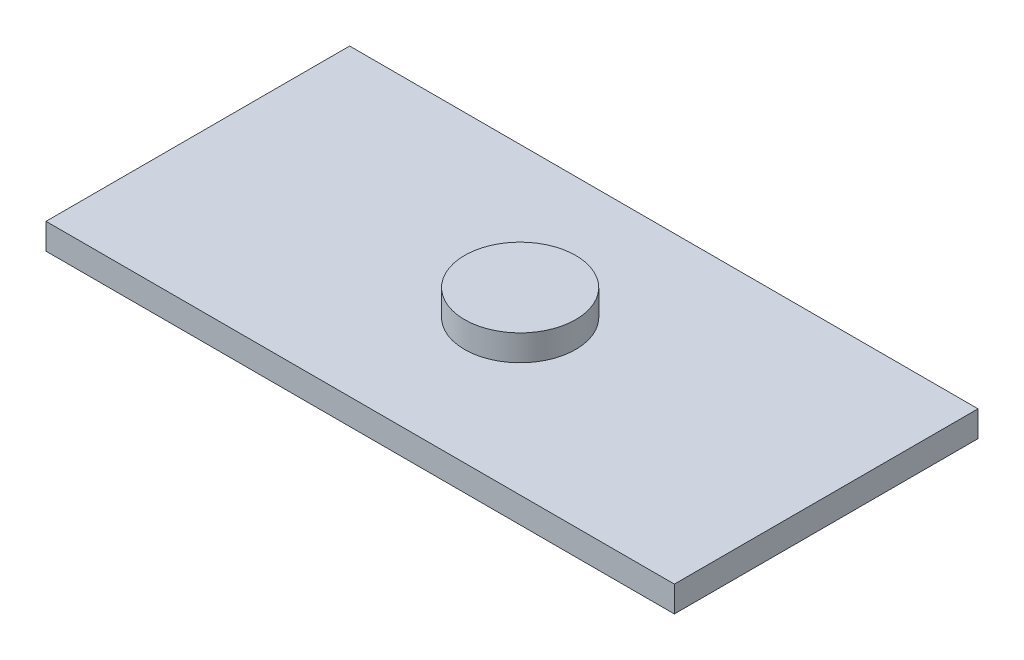
SolidWorks part; units mm, degrees
ref_plane "Front Plane" through (0, 0, 0) normal (0, 0, 1) x (1, 0, 0)
ref_plane "Top Plane" through (0, 0, 0) normal (0, 1, 0) x (1, 0, 0)
ref_plane "Right Plane" through (0, 0, 0) normal (1, 0, 0) x (0, 0, -1)
sketch "Sketch1" plane through (0, 0, 0) normal (0, 1, 0) x (1, 0, 0)
  line L1 (0, 0) -> (60.6751, 0)
  line L2 (0, 0) -> (0, 29.3195)
  line L3 (0, 29.3195) -> (60.6751, 29.3195)
  line L4 (60.6751, 0) -> (60.6751, 29.3195)
extrude "Boss-Extrude1" add sketch "Sketch1" along normal blind 2.5
sketch "Sketch2" plane through (0, 2.5, 0) normal (0, 1, 0) x (1, 0, 0)
  circle A0 centre (30.9271, 14.8563) radius 5.3692
extrude "Boss-Extrude2" add sketch "Sketch2" along normal blind 2.5
